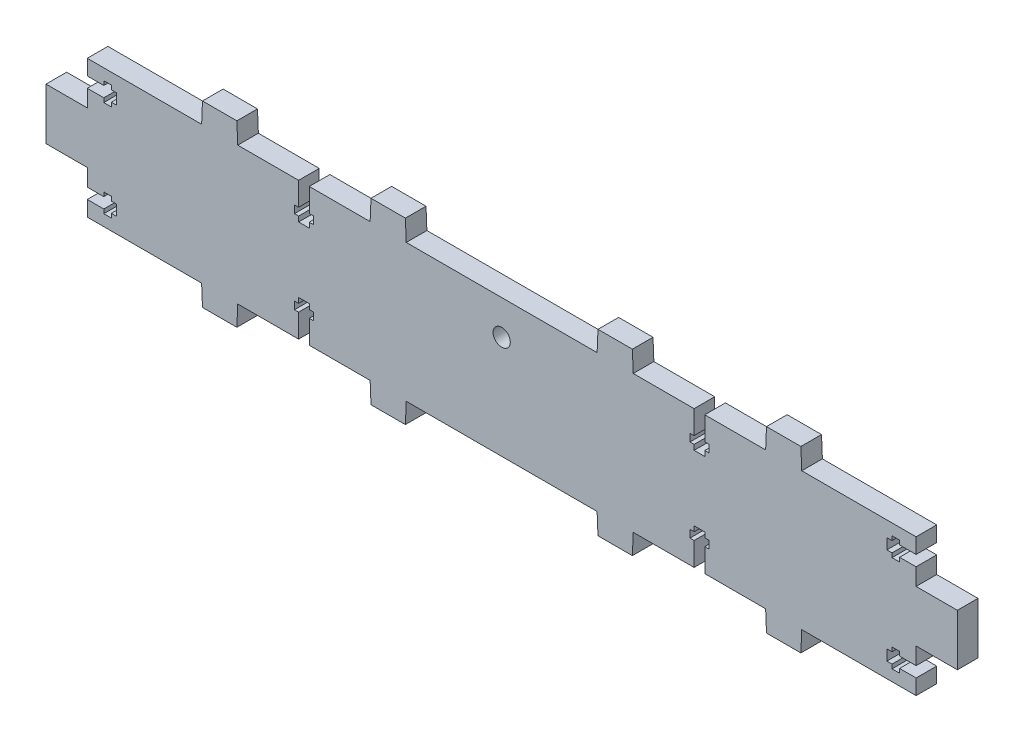
SolidWorks part; units mm, degrees
ref_plane "Front" through (0, 0, 0) normal (0, 0, 1) x (1, 0, 0)
ref_plane "Top" through (0, 0, 0) normal (0, 1, 0) x (1, 0, 0)
ref_plane "Right" through (0, 0, 0) normal (1, 0, 0) x (0, 0, -1)
sketch "Эскиз1" plane through (0, 0, 0) normal (0, 0, 1) x (1, 0, 0)
  line L0 (-28, -26) -> (-27.75, -20)
  line L1 (-38, -26) -> (-28, -26)
  line L2 (-38.25, -20) -> (-38, -26)
  line L3 (-43.45, -20) -> (-38.25, -20)
  line L4 (-55.95, -13.2) -> (-55.95, -20)
  line L5 (-54.75, -13.2) -> (-55.95, -13.2)
  line L6 (-54.75, -11) -> (-54.75, -13.2)
  line L7 (-55.95, -11) -> (-54.75, -11)
  line L8 (-55.95, -9.5) -> (-55.95, -11)
  line L9 (-59.05, -9.5) -> (-55.95, -9.5)
  line L10 (-59.05, -11) -> (-59.05, -9.5)
  line L11 (-60.25, -11) -> (-59.05, -11)
  line L12 (-60.25, -13.2) -> (-60.25, -11)
  line L13 (-59.05, -13.2) -> (-60.25, -13.2)
  line L14 (-59.05, -20) -> (-59.05, -13.2)
  line L15 (-76.75, -20) -> (-71.55, -20)
  line L16 (-77, -26) -> (-76.75, -20)
  line L17 (-87, -26) -> (-77, -26)
  line L18 (-87.25, -20) -> (-87, -26)
  line L19 (-120.5, -20) -> (-87.25, -20)
  line L20 (-120.5, -15.55) -> (-120.5, -20)
  line L21 (-115.7, -15.55) -> (-120.5, -15.55)
  line L22 (-115.7, -16.75) -> (-115.7, -15.55)
  line L23 (-113.5, -16.75) -> (-115.7, -16.75)
  line L24 (-113.5, -15.55) -> (-113.5, -16.75)
  line L25 (-112, -15.55) -> (-113.5, -15.55)
  line L26 (-112, -12.45) -> (-112, -15.55)
  line L27 (-113.5, -12.45) -> (-112, -12.45)
  line L28 (-113.5, -11.25) -> (-113.5, -12.45)
  line L29 (-115.7, -11.25) -> (-113.5, -11.25)
  line L30 (-115.7, -12.45) -> (-115.7, -11.25)
  line L31 (-120.5, -12.45) -> (-115.7, -12.45)
  line L32 (-132.5, -7.5) -> (-120.5, -7.5)
  line L33 (-132.5, 7.5) -> (-132.5, -7.5)
  line L34 (-120.5, 7.5) -> (-132.5, 7.5)
  line L35 (-120.5, 12.45) -> (-120.5, 7.5)
  line L36 (-115.7, 12.45) -> (-120.5, 12.45)
  line L37 (-115.7, 11.25) -> (-115.7, 12.45)
  line L38 (-113.5, 11.25) -> (-115.7, 11.25)
  line L39 (-113.5, 12.45) -> (-113.5, 11.25)
  line L40 (-112, 12.45) -> (-113.5, 12.45)
  line L41 (-112, 15.55) -> (-112, 12.45)
  line L42 (-113.5, 15.55) -> (-112, 15.55)
  line L43 (-113.5, 16.75) -> (-113.5, 15.55)
  line L44 (-115.7, 16.75) -> (-113.5, 16.75)
  line L45 (-115.7, 15.55) -> (-115.7, 16.75)
  line L46 (-120.5, 15.55) -> (-115.7, 15.55)
  line L47 (-120.5, 20) -> (-120.5, 15.55)
  line L48 (-87.25, 20) -> (-120.5, 20)
  line L49 (-87, 26) -> (-87.25, 20)
  line L50 (-77, 26) -> (-87, 26)
  line L51 (-76.75, 20) -> (-77, 26)
  line L52 (-71.55, 20) -> (-76.75, 20)
  line L53 (-59.05, 13.2) -> (-59.05, 20)
  line L54 (-60.25, 13.2) -> (-59.05, 13.2)
  line L55 (-60.25, 11) -> (-60.25, 13.2)
  line L56 (-59.05, 11) -> (-60.25, 11)
  line L57 (-59.05, 9.5) -> (-59.05, 11)
  line L58 (-55.95, 9.5) -> (-59.05, 9.5)
  line L59 (-55.95, 11) -> (-55.95, 9.5)
  line L60 (-54.75, 11) -> (-55.95, 11)
  line L61 (-54.75, 13.2) -> (-54.75, 11)
  line L62 (-55.95, 13.2) -> (-54.75, 13.2)
  line L63 (-55.95, 20) -> (-55.95, 13.2)
  line L64 (-38.25, 20) -> (-43.45, 20)
  line L65 (-38, 26) -> (-38.25, 20)
  line L66 (-28, 26) -> (-38, 26)
  line L67 (-27.75, 20) -> (-28, 26)
  line L68 (27.75, 20) -> (28, 26)
  line L69 (28, 26) -> (38, 26)
  line L70 (38, 26) -> (38.25, 20)
  line L71 (38.25, 20) -> (43.45, 20)
  line L72 (55.95, 20) -> (55.95, 13.2)
  line L73 (55.95, 13.2) -> (54.75, 13.2)
  line L74 (54.75, 13.2) -> (54.75, 11)
  line L75 (54.75, 11) -> (55.95, 11)
  line L76 (55.95, 11) -> (55.95, 9.5)
  line L77 (55.95, 9.5) -> (59.05, 9.5)
  line L78 (59.05, 9.5) -> (59.05, 11)
  line L79 (59.05, 11) -> (60.25, 11)
  line L80 (60.25, 11) -> (60.25, 13.2)
  line L81 (60.25, 13.2) -> (59.05, 13.2)
  line L82 (59.05, 13.2) -> (59.05, 20)
  line L83 (59.05, 20) -> (64.25, 20)
  line L84 (76.75, 20) -> (77, 26)
  line L85 (77, 26) -> (87, 26)
  line L86 (87, 26) -> (87.25, 20)
  line L87 (87.25, 20) -> (120.5, 20)
  line L88 (120.5, 20) -> (120.5, 15.55)
  line L89 (120.5, 15.55) -> (115.7, 15.55)
  line L90 (115.7, 15.55) -> (115.7, 16.75)
  line L91 (115.7, 16.75) -> (113.5, 16.75)
  line L92 (113.5, 16.75) -> (113.5, 15.55)
  line L93 (113.5, 15.55) -> (112, 15.55)
  line L94 (112, 15.55) -> (112, 12.45)
  line L95 (112, 12.45) -> (113.5, 12.45)
  line L96 (113.5, 12.45) -> (113.5, 11.25)
  line L97 (113.5, 11.25) -> (115.7, 11.25)
  line L98 (115.7, 11.25) -> (115.7, 12.45)
  line L99 (115.7, 12.45) -> (120.5, 12.45)
  line L100 (120.5, 12.45) -> (120.5, 7.5)
  line L101 (120.5, 7.5) -> (132.5, 7.5)
  line L102 (132.5, 7.5) -> (132.5, -7.5)
  line L103 (132.5, -7.5) -> (120.5, -7.5)
  line L104 (120.5, -12.45) -> (115.7, -12.45)
  line L105 (115.7, -12.45) -> (115.7, -11.25)
  line L106 (115.7, -11.25) -> (113.5, -11.25)
  line L107 (113.5, -11.25) -> (113.5, -12.45)
  line L108 (113.5, -12.45) -> (112, -12.45)
  line L109 (112, -12.45) -> (112, -15.55)
  line L110 (112, -15.55) -> (113.5, -15.55)
  line L111 (113.5, -15.55) -> (113.5, -16.75)
  line L112 (113.5, -16.75) -> (115.7, -16.75)
  line L113 (115.7, -16.75) -> (115.7, -15.55)
  line L114 (115.7, -15.55) -> (120.5, -15.55)
  line L115 (120.5, -15.55) -> (120.5, -20)
  line L116 (120.5, -20) -> (87.25, -20)
  line L117 (87.25, -20) -> (87, -26)
  line L118 (87, -26) -> (77, -26)
  line L119 (77, -26) -> (76.75, -20)
  line L120 (64.25, -20) -> (59.05, -20)
  line L121 (59.05, -20) -> (59.05, -13.2)
  line L122 (59.05, -13.2) -> (60.25, -13.2)
  line L123 (60.25, -13.2) -> (60.25, -11)
  line L124 (60.25, -11) -> (59.05, -11)
  line L125 (59.05, -11) -> (59.05, -9.5)
  line L126 (59.05, -9.5) -> (55.95, -9.5)
  line L127 (55.95, -9.5) -> (55.95, -11)
  line L128 (55.95, -11) -> (54.75, -11)
  line L129 (54.75, -11) -> (54.75, -13.2)
  line L130 (54.75, -13.2) -> (55.95, -13.2)
  line L131 (55.95, -13.2) -> (55.95, -20)
  line L132 (43.45, -20) -> (38.25, -20)
  line L133 (38.25, -20) -> (38, -26)
  line L134 (38, -26) -> (28, -26)
  line L135 (28, -26) -> (27.75, -20)
  line L136 (76.75, -20) -> (64.25, -20)
  line L137 (55.95, -20) -> (43.45, -20)
  line L138 (43.45, 20) -> (55.95, 20)
  line L139 (76.75, 20) -> (64.25, 20)
  line L140 (-43.45, -20) -> (-55.95, -20)
  line L141 (-71.55, -20) -> (-59.05, -20)
  line L142 (-43.45, 20) -> (-55.95, 20)
  line L143 (-59.05, 20) -> (-71.55, 20)
  line L144 (120.5, -12.45) -> (120.5, -7.5)
  line L145 (-120.5, -12.45) -> (-120.5, -7.5)
  line L146 (27.75, 20) -> (-27.75, 20)
  line L147 (27.75, -20) -> (-27.75, -20)
  circle A0 centre (0, 10) radius 2.5
extrude "Бобышка-Вытянуть1" add sketch "Эскиз1" along normal blind 6
